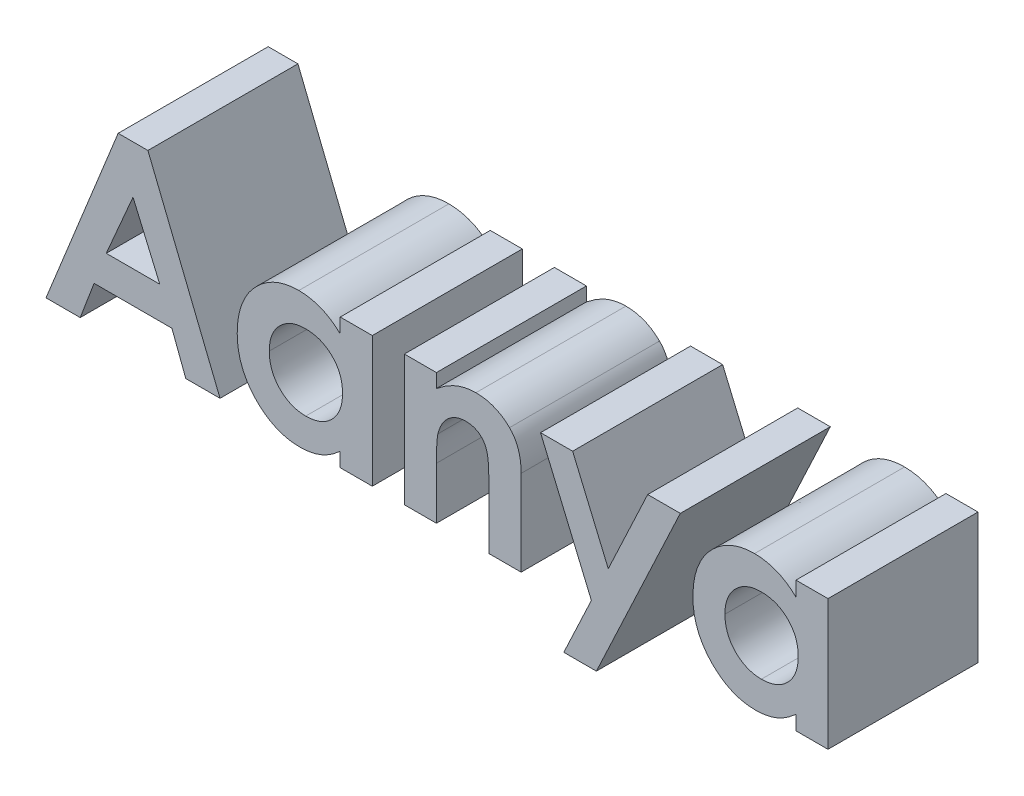
SolidWorks part; units mm, degrees
ref_plane "Front Plane" through (0, 0, 0) normal (0, 0, 1) x (1, 0, 0)
ref_plane "Top Plane" through (0, 0, 0) normal (0, 1, 0) x (1, 0, 0)
ref_plane "Right Plane" through (0, 0, 0) normal (1, 0, 0) x (0, 0, -1)
sketch "Sketch1" plane through (0, 0, 0) normal (0, 0, 1) x (1, 0, 0)
  line L0 (-8.9502, 2.9728) -> (-8.1574, 2.9728)
  line L1 (-15, -5) -> (15, -5)
  line L2 (-15, -5) -> (-15, 5)
  line L3 (-15, 5) -> (15, 5)
  line L4 (15, -5) -> (15, 5)
  line L5 (-14.4279, -5.432) -> (15.5721, 4.568) construction
  line L6 (-14.4279, 4.568) -> (15.5721, -5.432) construction
  line L7 (-8.1574, 2.9728) -> (-6.2341, -1.7897)
  line L8 (-6.2341, -1.7897) -> (-7.1471, -1.7897)
  line L9 (-7.1471, -1.7897) -> (-7.5173, -0.8128)
  line L10 (-7.5173, -0.8128) -> (-9.5923, -0.8128)
  line L11 (-9.5923, -0.8128) -> (-9.9624, -1.7897)
  line L12 (-9.9624, -1.7897) -> (-10.8745, -1.7897)
  line L13 (-10.8745, -1.7897) -> (-8.9502, 2.9728)
  line L14 (-8.5543, 1.6954) -> (-9.2679, 0.042)
  line L15 (-9.2679, 0.042) -> (-7.8407, 0.042)
  line L16 (-7.8407, 0.042) -> (-8.5543, 1.6954)
  line L17 (-3.0286, 1.6906) -> (-2.1738, 1.6906)
  line L18 (-2.1738, 1.6906) -> (-2.1738, -1.7897)
  line L19 (-2.1738, -1.7897) -> (-3.0286, -1.7897)
  line L20 (-3.0286, -1.7897) -> (-3.0286, -1.41)
  line L21 (-3.0286, 1.2985) -> (-3.0286, 1.6906)
  line L22 (-1.319, 1.6906) -> (-0.4642, 1.6906)
  line L23 (-0.4642, 1.6906) -> (-0.4642, 1.3223)
  line L24 (1.795, 0.4923) -> (1.795, -1.7897)
  line L25 (1.795, -1.7897) -> (0.9402, -1.7897)
  line L26 (0.9402, -1.7897) -> (0.9402, -0.2785)
  line L27 (-0.4642, -0.4045) -> (-0.4642, -1.7897)
  line L28 (-0.4642, -1.7897) -> (-1.319, -1.7897)
  line L29 (-1.319, -1.7897) -> (-1.319, 1.6906)
  line L30 (2.3121, 1.6906) -> (3.1678, 1.6906)
  line L31 (3.1678, 1.6906) -> (4.118, -0.5485)
  line L32 (4.118, -0.5485) -> (5.1694, 1.6906)
  line L33 (5.1694, 1.6906) -> (6.0385, 1.6906)
  line L34 (6.0385, 1.6906) -> (3.8013, -3.0719)
  line L35 (3.8013, -3.0719) -> (2.9322, -3.0719)
  line L36 (2.9322, -3.0719) -> (3.6677, -1.5064)
  line L37 (3.6677, -1.5064) -> (2.3121, 1.6906)
  line L38 (9.1219, 1.6906) -> (9.9767, 1.6906)
  line L39 (9.9767, 1.6906) -> (9.9767, -1.7897)
  line L40 (9.9767, -1.7897) -> (9.1219, -1.7897)
  line L41 (9.1219, -1.7897) -> (9.1219, -1.41)
  line L42 (9.1219, 1.2985) -> (9.1219, 1.6906)
  spline S0 degree 3 poles (-3.0286, -1.41) (-3.1094, -1.483) (-3.2341, -1.5832) (-3.4126, -1.6885) (-3.5435, -1.7497) (-3.6774, -1.7948) (-3.8637, -1.8392) (-4.0089, -1.8501) (-4.1066, -1.8508) knots 0 0 0 0 0.273944 0.399987 0.519719 0.636176 0.754371 1 1 1 1
  spline S1 degree 3 poles (-4.1066, -1.8508) (-4.2168, -1.8519) (-4.3802, -1.8351) (-4.5903, -1.7809) (-4.7407, -1.7245) (-4.8852, -1.6512) (-5.0248, -1.5632) (-5.1571, -1.4573) (-5.2833, -1.338) (-5.3989, -1.2068) (-5.4999, -1.0656) (-5.585, -0.9162) (-5.6548, -0.7592) (-5.7096, -0.5947) (-5.7628, -0.3613) (-5.7758, -0.1791) (-5.7762, -0.0562) knots 0 0 0 0 0.121092 0.179634 0.238304 0.297437 0.357507 0.419513 0.4836 0.548295 0.611487 0.674313 0.737107 0.80016 0.864737 1 1 1 1
  spline S2 degree 3 poles (-5.7762, -0.0562) (-5.7752, 0.0703) (-5.7638, 0.2579) (-5.7114, 0.4979) (-5.6591, 0.6657) (-5.5918, 0.8245) (-5.5097, 0.9747) (-5.4119, 1.1158) (-5.2992, 1.2454) (-5.1775, 1.3642) (-5.0473, 1.4677) (-4.9107, 1.5555) (-4.7674, 1.6273) (-4.6175, 1.6827) (-4.4074, 1.7376) (-4.243, 1.7518) (-4.1324, 1.7516) knots 0 0 0 0 0.139309 0.205474 0.269598 0.332253 0.39483 0.457376 0.520582 0.583374 0.644082 0.70304 0.761664 0.819844 0.878346 1 1 1 1
  spline S3 degree 3 poles (-4.1324, 1.7516) (-4.0296, 1.7528) (-3.8772, 1.7376) (-3.6803, 1.6902) (-3.5392, 1.6403) (-3.4023, 1.5772) (-3.2258, 1.4705) (-3.1038, 1.3723) (-3.0286, 1.2985) knots 0 0 0 0 0.251537 0.373434 0.495667 0.61768 0.742091 1 1 1 1
  spline S4 degree 3 poles (-3.953, 0.9579) (-4.0197, 0.9568) (-4.1188, 0.9503) (-4.2459, 0.9208) (-4.3347, 0.8887) (-4.4198, 0.8496) (-4.4999, 0.8007) (-4.5757, 0.7429) (-4.6467, 0.6775) (-4.7115, 0.6057) (-4.7673, 0.5273) (-4.8148, 0.4445) (-4.8549, 0.357) (-4.8836, 0.2638) (-4.9145, 0.1313) (-4.9199, 0.0272) (-4.9214, -0.0429) knots 0 0 0 0 0.128421 0.189996 0.250359 0.309744 0.369856 0.430537 0.492876 0.555257 0.616197 0.677577 0.738631 0.800922 0.864882 1 1 1 1
  spline S5 degree 3 poles (-4.9214, -0.0429) (-4.9201, -0.1136) (-4.914, -0.2184) (-4.8842, -0.3528) (-4.8522, -0.4464) (-4.8132, -0.5357) (-4.7656, -0.6204) (-4.7072, -0.6988) (-4.6424, -0.7729) (-4.5699, -0.839) (-4.4937, -0.8978) (-4.4127, -0.9469) (-4.3277, -0.9866) (-4.2392, -1.019) (-4.1133, -1.0481) (-4.0154, -1.0567) (-3.9492, -1.057) knots 0 0 0 0 0.135365 0.199461 0.262264 0.323991 0.385461 0.447171 0.510418 0.573171 0.634271 0.693954 0.753723 0.813084 0.873629 1 1 1 1
  spline S6 degree 3 poles (-3.9492, -1.057) (-3.8813, -1.0559) (-3.7806, -1.0495) (-3.6516, -1.0199) (-3.5616, -0.9876) (-3.4753, -0.9489) (-3.3935, -0.9009) (-3.3171, -0.8432) (-3.2457, -0.7772) (-3.1802, -0.7048) (-3.1236, -0.6254) (-3.0743, -0.5416) (-3.0356, -0.4513) (-3.0048, -0.3561) (-2.9747, -0.2194) (-2.9688, -0.1123) (-2.9675, -0.04) knots 0 0 0 0 0.128662 0.18979 0.249707 0.309189 0.3685 0.428644 0.489937 0.552121 0.612878 0.67405 0.735729 0.798305 0.862953 1 1 1 1
  spline S7 degree 3 poles (-2.9675, -0.04) (-2.9688, 0.0307) (-2.9747, 0.1356) (-3.005, 0.2697) (-3.0351, 0.3632) (-3.0746, 0.4513) (-3.1239, 0.5331) (-3.1799, 0.6115) (-3.2461, 0.6819) (-3.3171, 0.7474) (-3.3947, 0.8033) (-3.4763, 0.8516) (-3.5625, 0.8912) (-3.654, 0.9202) (-3.7834, 0.9508) (-3.8849, 0.9567) (-3.953, 0.9579) knots 0 0 0 0 0.135096 0.199063 0.261548 0.322044 0.382646 0.443385 0.505155 0.566516 0.627254 0.687026 0.74697 0.807539 0.869733 1 1 1 1
  spline S8 degree 3 poles (-0.4642, 1.3223) (-0.3723, 1.3964) (-0.2344, 1.4949) (-0.0468, 1.6008) (0.082, 1.6584) (0.2082, 1.6997) (0.3754, 1.7396) (0.5036, 1.7522) (0.5891, 1.7516) knots 0 0 0 0 0.304989 0.436681 0.556242 0.668759 0.779379 1 1 1 1
  spline S9 degree 3 poles (0.5891, 1.7516) (0.6739, 1.7507) (0.8004, 1.7425) (0.9621, 1.7029) (1.0774, 1.6641) (1.1873, 1.6128) (1.3298, 1.5311) (1.4247, 1.4502) (1.4849, 1.3929) knots 0 0 0 0 0.257369 0.381171 0.503299 0.625248 0.747811 1 1 1 1
  spline S10 degree 3 poles (1.4849, 1.3929) (1.5366, 1.3416) (1.6053, 1.2546) (1.6763, 1.1234) (1.7205, 1.0151) (1.7531, 0.8967) (1.7877, 0.7227) (1.7944, 0.5857) (1.795, 0.4923) knots 0 0 0 0 0.22321 0.337546 0.456528 0.581244 0.713405 1 1 1 1
  spline S11 degree 3 poles (0.9402, -0.2785) (0.9399, -0.1841) (0.9391, -0.0488) (0.9318, 0.1225) (0.9271, 0.2317) (0.9178, 0.3277) (0.9094, 0.411) (0.8965, 0.4809) (0.8798, 0.5561) (0.8506, 0.6365) (0.8052, 0.7214) (0.7476, 0.7934) (0.6803, 0.8532) (0.6031, 0.9005) (0.4852, 0.9464) (0.3885, 0.9582) (0.3229, 0.9579) knots 0 0 0 0 0.179518 0.256937 0.32593 0.387213 0.440139 0.484952 0.522188 0.586422 0.647004 0.704202 0.760716 0.817414 0.875213 1 1 1 1
  spline S12 degree 3 poles (0.3229, 0.9579) (0.2364, 0.957) (0.1061, 0.938) (-0.0494, 0.8615) (-0.1536, 0.7834) (-0.2455, 0.6869) (-0.35, 0.5288) (-0.4008, 0.3921) (-0.4241, 0.2958) knots 0 0 0 0 0.240658 0.35739 0.477137 0.600009 0.725225 1 1 1 1
  spline S13 degree 3 poles (-0.4241, 0.2958) (-0.4331, 0.2614) (-0.4397, 0.2029) (-0.4502, 0.1176) (-0.4536, 0.036) (-0.4593, -0.0574) (-0.4623, -0.2057) (-0.4641, -0.3227) (-0.4642, -0.4045) knots 0 0 0 0 0.151476 0.251213 0.366854 0.500124 0.650932 1 1 1 1
  spline S14 degree 3 poles (9.1219, -1.41) (9.041, -1.483) (8.9164, -1.5832) (8.7379, -1.6885) (8.607, -1.7497) (8.4731, -1.7948) (8.2868, -1.8392) (8.1415, -1.8501) (8.0438, -1.8508) knots 0 0 0 0 0.273944 0.399987 0.519719 0.636176 0.754371 1 1 1 1
  spline S15 degree 3 poles (8.0438, -1.8508) (7.9337, -1.8519) (7.7703, -1.8351) (7.5602, -1.7809) (7.4097, -1.7245) (7.2653, -1.6512) (7.1257, -1.5632) (6.9933, -1.4573) (6.8671, -1.338) (6.7516, -1.2068) (6.6506, -1.0656) (6.5654, -0.9162) (6.4957, -0.7592) (6.4408, -0.5947) (6.3877, -0.3613) (6.3747, -0.1791) (6.3743, -0.0562) knots 0 0 0 0 0.121092 0.179634 0.238304 0.297437 0.357507 0.419513 0.4836 0.548295 0.611487 0.674313 0.737107 0.80016 0.864737 1 1 1 1
  spline S16 degree 3 poles (6.3743, -0.0562) (6.3753, 0.0703) (6.3867, 0.2579) (6.439, 0.4979) (6.4914, 0.6657) (6.5587, 0.8245) (6.6407, 0.9747) (6.7385, 1.1158) (6.8513, 1.2454) (6.973, 1.3642) (7.1032, 1.4677) (7.2398, 1.5555) (7.3831, 1.6273) (7.5329, 1.6827) (7.7431, 1.7376) (7.9075, 1.7518) (8.0181, 1.7516) knots 0 0 0 0 0.139309 0.205474 0.269598 0.332253 0.39483 0.457376 0.520582 0.583374 0.644082 0.70304 0.761664 0.819844 0.878346 1 1 1 1
  spline S17 degree 3 poles (8.0181, 1.7516) (8.1209, 1.7528) (8.2732, 1.7376) (8.4702, 1.6902) (8.6113, 1.6403) (8.7482, 1.5772) (8.9247, 1.4705) (9.0467, 1.3723) (9.1219, 1.2985) knots 0 0 0 0 0.251537 0.373434 0.495667 0.61768 0.742091 1 1 1 1
  spline S18 degree 3 poles (8.1974, 0.9579) (8.1308, 0.9568) (8.0317, 0.9503) (7.9046, 0.9208) (7.8158, 0.8887) (7.7307, 0.8496) (7.6506, 0.8007) (7.5748, 0.7429) (7.5037, 0.6775) (7.439, 0.6057) (7.3832, 0.5273) (7.3357, 0.4445) (7.2956, 0.357) (7.2669, 0.2638) (7.236, 0.1313) (7.2306, 0.0272) (7.2291, -0.0429) knots 0 0 0 0 0.128421 0.189996 0.250359 0.309744 0.369856 0.430537 0.492876 0.555257 0.616197 0.677577 0.738631 0.800922 0.864882 1 1 1 1
  spline S19 degree 3 poles (7.2291, -0.0429) (7.2304, -0.1136) (7.2365, -0.2184) (7.2663, -0.3528) (7.2982, -0.4464) (7.3373, -0.5357) (7.3849, -0.6204) (7.4433, -0.6988) (7.5081, -0.7729) (7.5806, -0.839) (7.6568, -0.8978) (7.7378, -0.9469) (7.8227, -0.9866) (7.9113, -1.019) (8.0372, -1.0481) (8.1351, -1.0567) (8.2013, -1.057) knots 0 0 0 0 0.135365 0.199461 0.262264 0.323991 0.385461 0.447171 0.510418 0.573171 0.634271 0.693954 0.753723 0.813084 0.873629 1 1 1 1
  spline S20 degree 3 poles (8.2013, -1.057) (8.2692, -1.0559) (8.3699, -1.0495) (8.4988, -1.0199) (8.5888, -0.9876) (8.6751, -0.9489) (8.7569, -0.9009) (8.8334, -0.8432) (8.9048, -0.7772) (8.9703, -0.7048) (9.0268, -0.6254) (9.0761, -0.5416) (9.1149, -0.4513) (9.1457, -0.3561) (9.1758, -0.2194) (9.1817, -0.1123) (9.183, -0.04) knots 0 0 0 0 0.128662 0.18979 0.249707 0.309189 0.3685 0.428644 0.489937 0.552121 0.612878 0.67405 0.735729 0.798305 0.862953 1 1 1 1
  spline S21 degree 3 poles (9.183, -0.04) (9.1817, 0.0307) (9.1758, 0.1356) (9.1455, 0.2697) (9.1153, 0.3632) (9.0759, 0.4513) (9.0265, 0.5331) (8.9706, 0.6115) (8.9044, 0.6819) (8.8333, 0.7474) (8.7558, 0.8033) (8.6742, 0.8516) (8.588, 0.8912) (8.4965, 0.9202) (8.3671, 0.9508) (8.2656, 0.9567) (8.1974, 0.9579) knots 0 0 0 0 0.135096 0.199063 0.261548 0.322044 0.382646 0.443385 0.505155 0.566516 0.627254 0.687026 0.74697 0.807539 0.869733 1 1 1 1
  point P0 (0.5721, -0.432)
  dimension "D1" = 10
  dimension "D2" = 30
extrude "Boss-Extrude1" add sketch "Sketch1" along normal blind 4 contours L13 L12 L11 L10 L9 L8 L7 L0 L16 L15 L14 | S3 S2 S1 S0 L20 L19 L18 L17 L21 S7 S6 S5 S4 | S13 S12 S11 L26 L25 L24 S10 S9 S8 L23 L22 L29 L28 L27 | L37 L36 L35 L34 L33 L32 L31 L30 | S17 S16 S15 S14 L41 L40 L39 L38 L42 S21 S20 S19 S18
